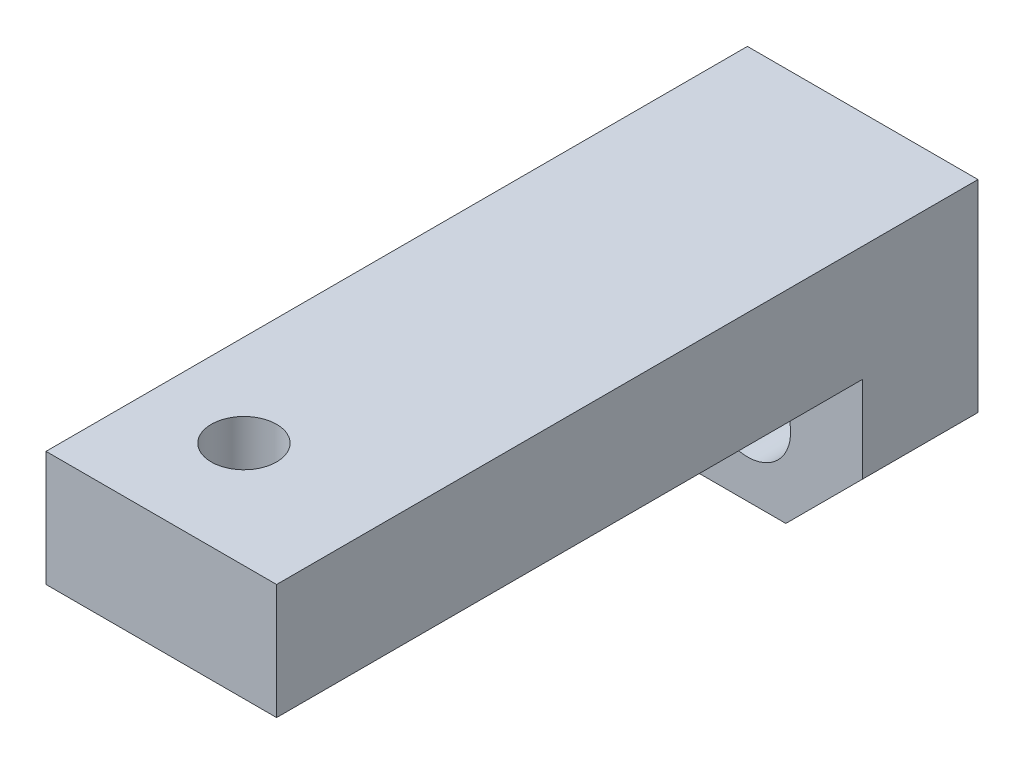
SolidWorks part; units mm, degrees
material "6061-T6 (SS)"
ref_plane "Front Plane" through (0, 0, 0) normal (0, 0, 1) x (1, 0, 0)
ref_plane "Top Plane" through (0, 0, 0) normal (0, 1, 0) x (1, 0, 0)
ref_plane "Right Plane" through (0, 0, 0) normal (1, 0, 0) x (0, 0, -1)
ref_plane "Plane1" through (7.22, 0, 0) normal (1, 0, 0) x (0, 0, -1)
sketch "Sketch1" plane through (7.22, 0, 0) normal (1, 0, 0) x (0, 0, -1)
  line L0 (0, 0) -> (-36.5, 0)
  line L1 (-36.5, 0) -> (-36.5, -14.5)
  line L2 (-36.5, -14.5) -> (0, -14.5)
  line L3 (0, -14.5) -> (0, 0)
  dimension "D1" = 36.5
  dimension "D2" = 14.5
  dimension "D3" = 36.5
  dimension "D4" = 14.5
extrude "Boss-Extrude1" add sketch "Sketch1" against normal blind 12
sketch "Sketch2" plane through (-4.78, 0, 0) normal (-1, 0, 0) x (0, 0, 1)
  line L0 (36.5, -6) -> (6, -6)
  line L1 (6, -6) -> (6, -14.5)
  line L2 (6, -14.5) -> (36.5, -14.5)
  line L3 (36.5, -14.5) -> (36.5, -6)
  line L4 (0, -14.5) -> (0, 0) construction
  line L5 (36.5, -14.5) -> (0, -14.5) construction
  dimension "D1" = 6
  dimension "D2" = 36.5
  dimension "D3" = 8.5
  dimension "D4" = 14.5
extrude "Cut-Extrude1" cut sketch "Sketch2" against normal through all
hole_wizard "Ø4.5 (4.5) Diameter Hole1" positions "Sketch4" profile "Sketch3" hole size "Ø4.5" standard "ANSI Metric"
sketch "Sketch4" plane through (0, 0, 0) normal (0, 0, -1) x (-1, 0, 0)
  point P0 (-1.22, -10.25)
  dimension "D1" = 1.22
  dimension "D2" = 10.25
sketch "Sketch3" plane through (1.22, -10.25, 0) normal (1, 0, 0) x (0, 1, 0)
  line L0 (0, 0) -> (0, 36.5)
  line L1 (0, 36.5) -> (2.25, 36.5)
  line L2 (2.25, 36.5) -> (2.25, 0)
  line L5 (2.25, 0) -> (0, 0)
  line L11 (0, -6.35) -> (0, 107.95) construction
  dimension "Thru Hole Dia." = 4.5
  dimension "Thru Hole Depth" = 36.5
hole_wizard "Ø3.4 (3.4) Diameter Hole1" positions "Sketch6" profile "Sketch5" hole size "Ø3.4" standard "ANSI Metric"
sketch "Sketch6" plane through (0, 0, 0) normal (0, 1, 0) x (1, 0, 0)
  point P0 (0, -30.98)
  dimension "D1" = 30.98
sketch "Sketch5" plane through (0, 0, 30.98) normal (1, 0, 0) x (0, 0, 1)
  line L0 (0, 0) -> (0, 14.5)
  line L1 (0, 14.5) -> (1.7, 14.5)
  line L2 (1.7, 14.5) -> (1.7, 0)
  line L5 (1.7, 0) -> (0, 0)
  line L11 (0, -6.35) -> (0, 107.95) construction
  dimension "Thru Hole Dia." = 3.4
  dimension "Thru Hole Depth" = 14.5
chamfer "Chamfer1" distance 4 angle 45 1 edges at (7.22, -14.5, 3)
